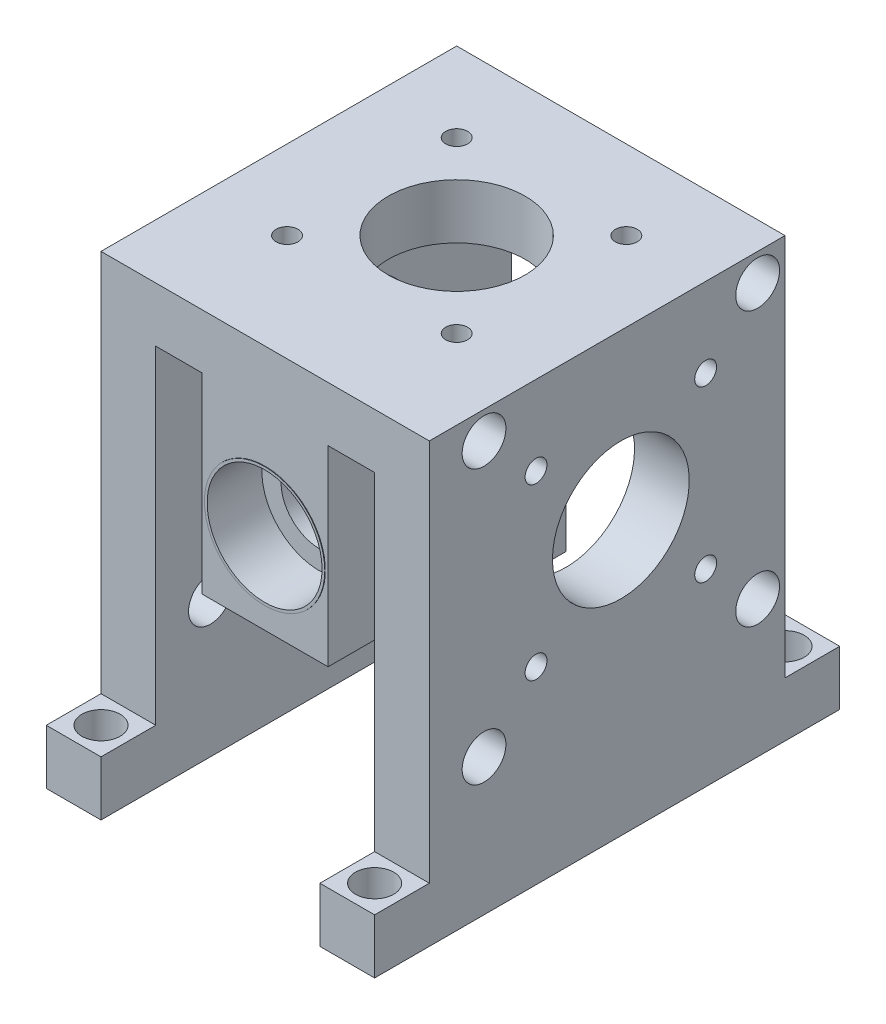
SolidWorks part; units mm, degrees
ref_plane "Alzado" through (0, 0, 0) normal (0, 0, 1) x (1, 0, 0)
ref_plane "Planta" through (0, 0, 0) normal (0, 1, 0) x (1, 0, 0)
ref_plane "Vista lateral" through (0, 0, 0) normal (1, 0, 0) x (0, 0, -1)
sketch "Croquis1" plane through (0, 0, 0) normal (0, 1, 0) x (1, 0, 0)
  line L1 (0, 0) -> (60, 0)
  line L2 (0, 0) -> (0, 65)
  line L3 (0, 65) -> (60, 65)
  line L4 (60, 0) -> (60, 65)
  dimension "D1" = 65
  dimension "D2" = 60
extrude "Saliente-Extruir1" add sketch "Croquis1" along normal blind 80
sketch "Croquis2" plane through (0, 0, 0) normal (-1, 0, 0) x (0, 0, 1)
  line L0 (-70, 0) -> (0, 0) construction
  line L1 (-70, 50) -> (0, 50) construction
  line L2 (-35, 109.7205) -> (-35, -21.8215) construction
  line L3 (-19.5, 65.5) -> (-50.5, 65.5) construction
  line L4 (-19.5, 65.5) -> (-19.5, 34.5) construction
  line L5 (-19.5, 34.5) -> (-50.5, 34.5) construction
  line L6 (-50.5, 65.5) -> (-50.5, 34.5) construction
  line L7 (-19.5, 65.5) -> (-50.5, 34.5) construction
  line L8 (-19.5, 34.5) -> (-50.5, 65.5) construction
  line L9 (-60, 75) -> (-10, 75) construction
  line L10 (-60, 75) -> (-60, 25) construction
  line L11 (-60, 25) -> (-10, 25) construction
  line L12 (-10, 75) -> (-10, 25) construction
  line L13 (-60, 75) -> (-10, 25) construction
  line L14 (-60, 25) -> (-10, 75) construction
  line L16 (0, 80) -> (0, 0) construction
  circle A0 centre (-35, 50) radius 12.5
  circle A1 centre (-50.5, 65.5) radius 2
  circle A2 centre (-19.5, 65.5) radius 2
  circle A3 centre (-19.5, 34.5) radius 2
  circle A4 centre (-50.5, 34.5) radius 2
  circle A5 centre (-60, 75) radius 4
  circle A6 centre (-10, 75) radius 4
  circle A7 centre (-10, 25) radius 4
  circle A8 centre (-60, 25) radius 4
  dimension "D2" = 25
  dimension "D5" = 4
  dimension "D9" = 8
  dimension "D3" = 31
  dimension "D4" = 31
  dimension "D6" = 35
  dimension "D7" = 50
  dimension "D8" = 50
  dimension "D1" = 50
extrude "Cortar-Extruir1" cut sketch "Croquis2" against normal through all
sketch "Croquis3" plane through (0, 0, -65) normal (0, 0, -1) x (-1, 0, 0)
  line L0 (-49, 70) -> (-11, 70)
  line L3 (-49, 70) -> (-49, 0)
  line L4 (-60, 80) -> (0, 80) construction
  line L5 (-11, 70) -> (-11, 0)
  line L6 (-60, 80) -> (-60, 0) construction
  line L7 (0, 80) -> (0, 0) construction
  line L8 (-49, 0) -> (-11, 0)
  dimension "D1" = 10
  dimension "D2" = 11
  dimension "D3" = 11
extrude "Cortar-Extruir4" cut sketch "Croquis3" against normal blind 50
sketch "Croquis4" plane through (0, 0, 0) normal (0, 0, 1) x (1, 0, 0)
  line L0 (0, 80) -> (0, 0) construction
  line L3 (0, 80) -> (60, 80) construction
  line L4 (0, 80) -> (60, 80) construction
  line L6 (60, 80) -> (60, 0) construction
  line L8 (10, 70) -> (18.5, 70)
  line L9 (10, 70) -> (10, 0)
  line L10 (50, 70) -> (50, 0)
  line L11 (30, 80) -> (30, 0) construction
  line L12 (0, 0) -> (60, 0) construction
  line L13 (18.5, 70) -> (18.5, 0)
  line L14 (10, 80) -> (10, 0) construction
  line L15 (10, 0) -> (18.5, 0)
  line L16 (50, 80) -> (50, 0) construction
  line L17 (41.5, 70) -> (41.5, 0)
  line L18 (41.5, 70) -> (50, 70)
  line L19 (18.5, 80) -> (18.5, 0) construction
  line L20 (41.5, 80) -> (41.5, 0) construction
  line L21 (15, 80) -> (15, 0) construction
  line L22 (41.5, 0) -> (50, 0)
  line L23 (45, 80) -> (45, 0) construction
  point P2 (0, 90)
  point P6 (33, 100)
  point P7 (33, 0)
  point P8 (57, 100)
  point P9 (57, 0)
  point P11 (60, 90)
  point P29 (18, 100)
  point P30 (18, 0)
  dimension "D1" = 10
  dimension "D2" = 5
  dimension "D3" = 5
  dimension "D4" = 3.5
  dimension "D5" = 15
  dimension "D6" = 10
  dimension "D7" = 15
  dimension "D8" = 3.5
extrude "Cortar-Extruir5" cut sketch "Croquis4" against normal through all
sketch "Croquis6" plane through (0, 80, 0) normal (0, 1, 0) x (1, 0, 0)
  line L0 (0, 0) -> (60, 0) construction
  line L1 (2.8131, 35) -> (57.1869, 35) construction
  line L3 (14.5, 50.5) -> (45.5, 50.5) construction
  line L4 (14.5, 50.5) -> (14.5, 19.5) construction
  line L5 (14.5, 19.5) -> (45.5, 19.5) construction
  line L6 (45.5, 50.5) -> (45.5, 19.5) construction
  line L7 (30, 19.5) -> (30, 50.5) construction
  line L8 (14.5, 35) -> (45.5, 35) construction
  circle A0 centre (30, 35) radius 12.5
  circle A1 centre (14.5, 50.5) radius 2
  circle A2 centre (45.5, 50.5) radius 2
  circle A3 centre (45.5, 19.5) radius 2
  circle A4 centre (14.5, 19.5) radius 2
  dimension "D2" = 25
  dimension "D5" = 4
  dimension "D1" = 35
  dimension "D3" = 31
  dimension "D4" = 31
extrude "Cortar-Extruir6" cut sketch "Croquis6" against normal through all
sketch "Croquis15" plane through (0, 0, 0) normal (0, 0, 1) x (1, 0, 0)
  line L0 (18.5, 0) -> (41.5, 0) construction
  line L1 (19, 50) -> (41, 50)
  circle A0 centre (30, 50) radius 11
  dimension "D1" = 50
extrude "Saliente-Extruir6" add sketch "Croquis15" along normal blind 0.1 contours A0
sketch "Croquis16" plane through (0, 0, 0.1) normal (0, 0, 1) x (1, 0, 0)
  circle A0 centre (30, 50) radius 10.5
  dimension "D1" = 21
extrude "Cortar-Extruir11" cut sketch "Croquis16" against normal blind 10
sketch "Croquis17" plane through (0, 0, -9.9) normal (0, 0, 1) x (1, 0, 0)
  circle A0 centre (30, 50) radius 7
  dimension "D1" = 14
extrude "Cortar-Extruir12" cut sketch "Croquis17" against normal up to next
sketch "Croquis10" plane through (0, 0, 0) normal (0, 0, 1) x (1, 0, 0)
  line L0 (41.5, 0) -> (18.5, 0)
  line L1 (41.5, 0) -> (41.5, 35)
  line L2 (18.5, 0) -> (18.5, 35)
  line L3 (41.5, 35) -> (18.5, 35)
  dimension "D1" = 35
extrude "Cortar-Extruir9" cut sketch "Croquis10" against normal through all
sketch "Croquis11" plane through (0, 0, 0) normal (0, 0, 1) x (1, 0, 0)
  line L0 (0, 0) -> (10, 0)
  line L1 (0, 0) -> (0, 10)
  line L2 (10, 0) -> (10, 10)
  line L3 (0, 10) -> (10, 10)
  line L4 (50, 0) -> (60, 0)
  line L5 (50, 0) -> (50, 10)
  line L6 (60, 0) -> (60, 10)
  line L7 (50, 10) -> (60, 10)
  dimension "D1" = 10
  dimension "D2" = 10
extrude "Saliente-Extruir4" add sketch "Croquis11" along normal blind 10
sketch "Sketch1" plane through (0, 10, 0) normal (0, 1, 0) x (1, 0, 0)
  line L0 (0, -10) -> (0, 0) construction
  line L3 (-4.1869, -5) -> (68.6385, -5) construction
  line L4 (60, -10) -> (50, -10) construction
  circle A0 centre (5, -5) radius 3.5
  circle A1 centre (55, -5) radius 3.5
  dimension "D2" = 7
  dimension "D4" = 50
  dimension "D1" = 5
  dimension "D3" = 5
extrude "Cut-Extrude1" cut sketch "Sketch1" against normal through all
ref_plane "Plano3" through (0, 0, -32.5) normal (0, 0, 1) x (1, 0, 0)
mirror "Mirror2" about plane through (0, 0, -32.5) normal (0, 0, 1) of "Cut-Extrude1", "Saliente-Extruir4"
